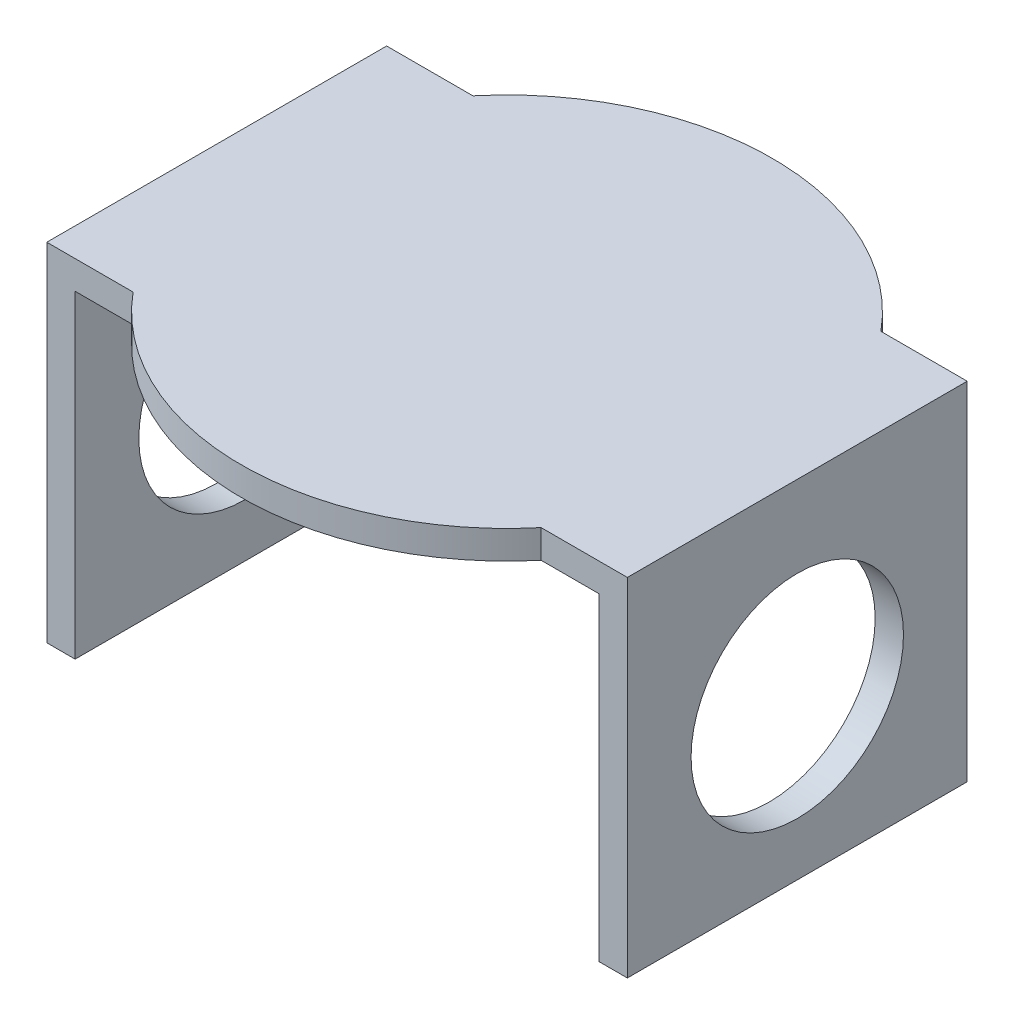
SolidWorks part; units mm, degrees
ref_plane "前视基准面" through (0, 0, 0) normal (0, 0, 1) x (1, 0, 0)
ref_plane "上视基准面" through (0, 0, 0) normal (0, 1, 0) x (1, 0, 0)
ref_plane "右视基准面" through (0, 0, 0) normal (1, 0, 0) x (0, 0, -1)
other "Configuration Table"
sketch "草图1" plane through (0, 0, 0) normal (0, 0, 1) x (1, 0, 0)
  line L0 (0, 0) -> (0, 107.8742) construction
  line L1 (-82, 98) -> (82, 98)
  line L2 (82, 98) -> (82, 0)
  line L3 (82, 0) -> (74, 0)
  line L4 (74, 0) -> (74, 90)
  line L5 (74, 90) -> (-74, 90)
  line L6 (-74, 0) -> (-74, 90)
  line L7 (-82, 0) -> (-74, 0)
  line L8 (-82, 98) -> (-82, 0)
  point P10 (0, 90)
  point P13 (0, 98)
  dimension "D1" = 8
  dimension "D2" = 8
  dimension "D3" = 90
  dimension "D4" = 82
extrude "凸台-拉伸1" add sketch "草图1" along normal blind 96
sketch "草图2" plane through (82, 0, 0) normal (1, 0, 0) x (0, 0, -1)
  line L0 (-105.5503, 45) -> (20.6011, 45) construction
  line L1 (-48, 100.8781) -> (-48, -4.975) construction
  line L2 (0, 0) -> (0, 98) construction
  line L3 (-96, 0) -> (-96, 98) construction
  line L4 (-96, 90) -> (0, 90) construction
  line L5 (-96, 98) -> (0, 98) construction
  line L7 (-96, 0) -> (0, 0) construction
  circle A0 centre (-48, 45) radius 30
  point P16 (0, 0)
  dimension "D2" = 60
  dimension "D1" = 8
extrude "切除-拉伸1" cut sketch "草图2" against normal blind 172
sketch "草图3" plane through (0, 98, 0) normal (0, 1, 0) x (1, 0, 0)
  line L0 (-96.0997, -48) -> (89.2664, -48) construction
  line L1 (0, 0) -> (0, -103.4147) construction
  line L2 (82, 0) -> (-82, 0) construction
  line L3 (82, -96) -> (-82, -96) construction
  circle A0 centre (0, -48) radius 75
  point P11 (0, 0)
  dimension "D1" = 150
extrude "凸台-拉伸2" add sketch "草图3" against normal up to surface (8 mm away) up to face at (0, 90, 48)
